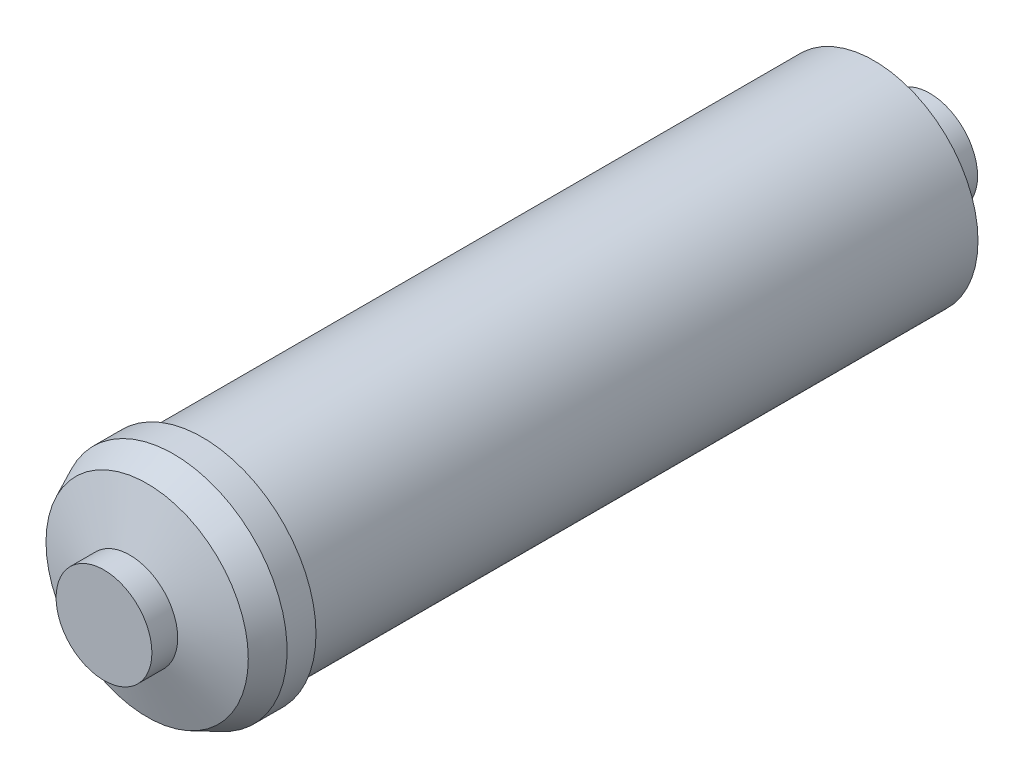
SolidWorks part; units mm, degrees
ref_plane "Front Plane" through (0, 0, 0) normal (0, 0, 1) x (1, 0, 0)
ref_plane "Top Plane" through (0, 0, 0) normal (0, 1, 0) x (1, 0, 0)
ref_plane "Right Plane" through (0, 0, 0) normal (1, 0, 0) x (0, 0, -1)
other "Configuration Table"
sketch "Sketch1" plane through (0, 0, 0) normal (0, 0, 1) x (1, 0, 0)
  circle A0 centre (0, 0) radius 14.732
  dimension "D1" = 29.464
extrude "Boss-Extrude1" add sketch "Sketch1" along normal blind 8.255
sketch "Sketch2" plane through (0, 0, 8.255) normal (0, 0, 1) x (1, 0, 0)
  circle A1 centre (0, 0) radius 14.732
  circle A2 centre (0, 0) radius 14.732
  dimension "D1" = 0
ref_plane "Plane1" through (0, 0, 17.145) normal (0, 0, 1) x (1, 0, 0)
sketch "Sketch3" plane through (0, 0, 17.145) normal (0, 0, 1) x (1, 0, 0)
  circle A0 centre (0, 0) radius 32.004
  dimension "D1" = 64.008
loft "Loft1" add profiles "Sketch2", "Sketch3"
sketch "Sketch4" plane through (0, 0, 17.145) normal (0, 0, 1) x (1, 0, 0)
  circle A1 centre (0, 0) radius 32.004
  circle A2 centre (0, 0) radius 32.004
  dimension "D1" = 0
extrude "Boss-Extrude2" add sketch "Sketch4" along normal blind 206.5782
sketch "Sketch5" plane through (0, 0, 223.7232) normal (0, 0, 1) x (1, 0, 0)
  circle A0 centre (0, 0) radius 34.925
  dimension "D1" = 69.85
extrude "Boss-Extrude3" add sketch "Sketch5" along normal blind 8.89
sketch "Sketch6" plane through (0, 0, 232.6132) normal (0, 0, 1) x (1, 0, 0)
  circle A1 centre (0, 0) radius 34.925
  circle A2 centre (0, 0) radius 34.925
  dimension "D1" = 0
ref_plane "Plane2" through (0, 0, 240.7412) normal (0, 0, 1) x (1, 0, 0)
sketch "Sketch7" plane through (0, 0, 240.7412) normal (0, 0, 1) x (1, 0, 0)
  circle A0 centre (0, 0) radius 31.115
  dimension "D1" = 62.23
loft "Loft2" add profiles "Sketch6", "Sketch7"
sketch "Sketch8" plane through (0, 0, 240.7412) normal (0, 0, 1) x (1, 0, 0)
  circle A1 centre (0, 0) radius 31.115
  circle A2 centre (0, 0) radius 31.115
  dimension "D1" = 0
ref_plane "Plane3" through (0, 0, 246.0752) normal (0, 0, 1) x (1, 0, 0)
sketch "Sketch9" plane through (0, 0, 246.0752) normal (0, 0, 1) x (1, 0, 0)
  circle A0 centre (0, 0) radius 14.732
  dimension "D1" = 29.464
loft "Loft3" add profiles "Sketch8", "Sketch9"
sketch "Sketch10" plane through (0, 0, 246.0752) normal (0, 0, 1) x (1, 0, 0)
  circle A1 centre (0, 0) radius 14.732
  circle A2 centre (0, 0) radius 14.732
  dimension "D1" = 0
extrude "Boss-Extrude4" add sketch "Sketch10" along normal blind 7.9375
